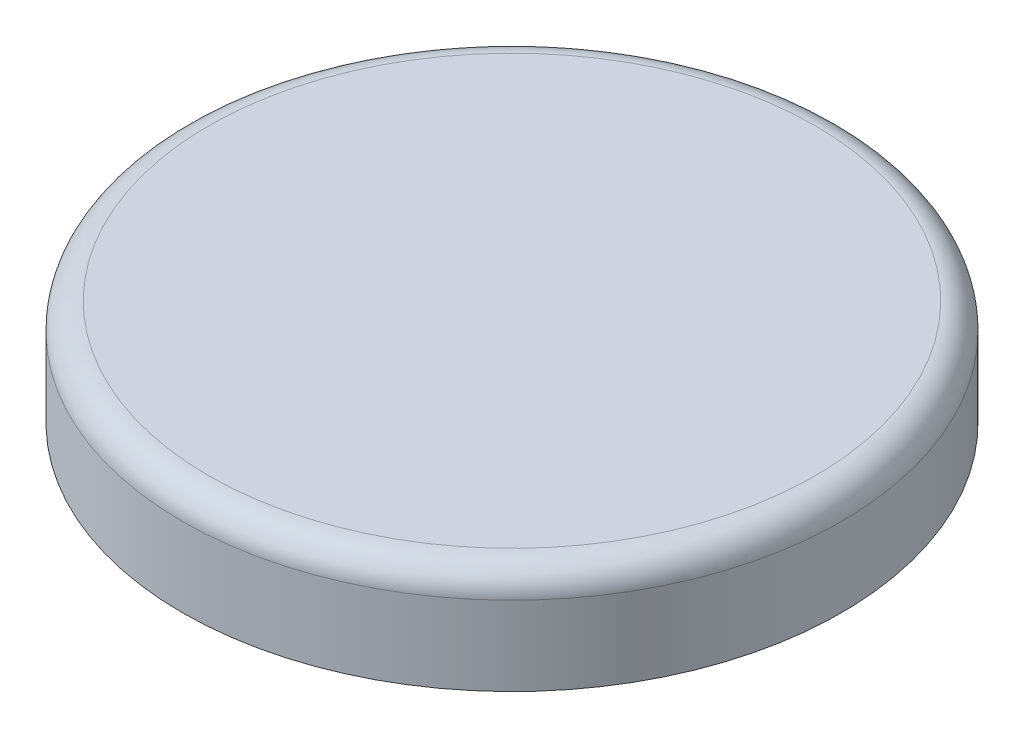
SolidWorks part; units mm, degrees
ref_plane "Alzado" through (0, 0, 0) normal (0, 0, 1) x (1, 0, 0)
ref_plane "Planta" through (0, 0, 0) normal (0, 1, 0) x (1, 0, 0)
ref_plane "Vista lateral" through (0, 0, 0) normal (1, 0, 0) x (0, 0, -1)
sketch "Croquis1" plane through (0, 0, 0) normal (0, 1, 0) x (1, 0, 0)
  circle A0 centre (0, 0) radius 125
  dimension "D1" = 250
extrude "Saliente-Extruir1" add sketch "Croquis1" along normal blind 40
sketch "Croquis2" plane through (0, 0, 0) normal (0, -1, 0) x (1, 0, 0)
  circle A0 centre (0, 0) radius 100
  dimension "D1" = 200
extrude "Cortar-Extruir1" cut sketch "Croquis2" against normal blind 30
fillet "Redondeo1" radius 10 1 edges at (0, 40, 125)
